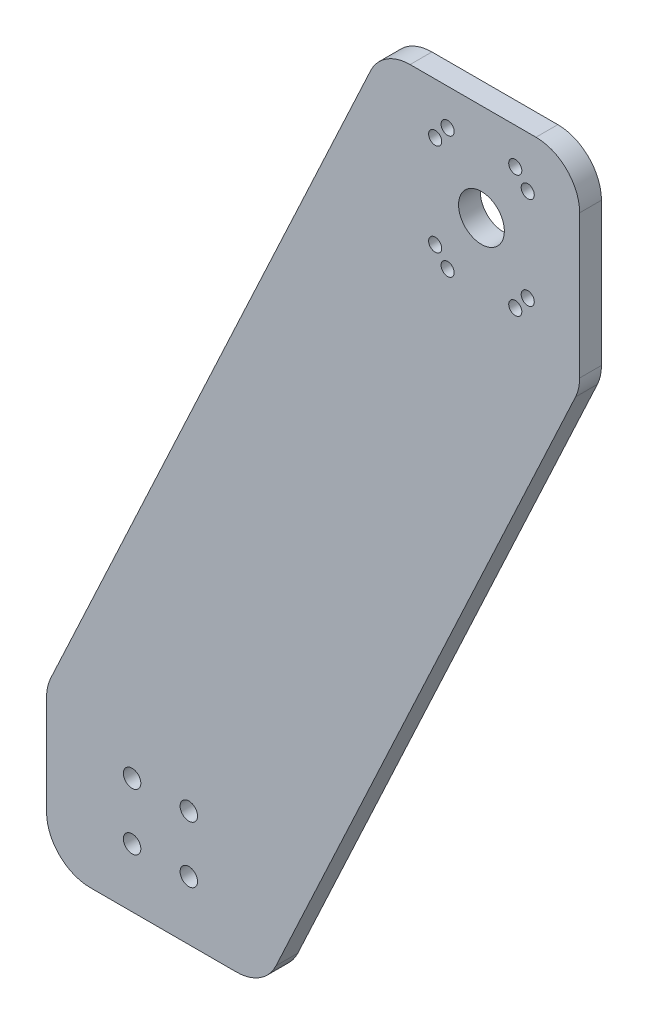
SolidWorks part; units mm, degrees
ref_plane "Piano frontale" through (0, 0, 0) normal (0, 0, 1) x (1, 0, 0)
ref_plane "Piano superiore" through (0, 0, 0) normal (0, 1, 0) x (1, 0, 0)
ref_plane "Piano destro" through (0, 0, 0) normal (1, 0, 0) x (0, 0, -1)
sketch "Schizzo1" plane through (0, 0, 0) normal (0, 0, 1) x (1, 0, 0)
  line L0 (20, 0) -> (87.0224, 0)
  line L1 (105.1486, 11.5476) -> (242.4453, 305.9815)
  line L2 (244.3192, 314.4339) -> (244.3192, 380)
  line L3 (224.3192, 400) -> (166.6229, 400)
  line L4 (0, 65.5661) -> (0, 20)
  line L5 (148.4968, 388.4524) -> (1.8738, 74.0185)
  line L6 (217.8585, 395.2269) -> (-13.8202, -101.6096) construction
  line L7 (11.433, 40) -> (107.7325, 40) construction
  line L8 (52.2134, 40) -> (52.2134, 85.084) construction
  line L9 (199.3192, 355.4693) -> (170.8286, 383.9599) construction
  line L10 (199.3192, 355.4693) -> (160.9701, 355.4693) construction
  line L11 (199.3192, 355.4693) -> (199.3192, 398.3848) construction
  line L13 (214.8192, 327.4693) -> (183.8192, 327.4693) construction
  line L14 (214.8192, 327.4693) -> (214.8192, 383.4693) construction
  line L15 (214.8192, 383.4693) -> (183.8192, 383.4693) construction
  line L16 (183.8192, 327.4693) -> (183.8192, 383.4693) construction
  line L17 (214.8192, 327.4693) -> (183.8192, 383.4693) construction
  line L18 (214.8192, 383.4693) -> (183.8192, 327.4693) construction
  circle A0 centre (39.2134, 53) radius 4
  circle A1 centre (65.2134, 53) radius 4
  circle A2 centre (65.2134, 27) radius 4
  circle A3 centre (39.2134, 27) radius 4
  circle A4 centre (199.3192, 355.4693) radius 10.5
  circle A5 centre (199.3192, 355.4693) radius 30 construction
  arc A6 (105.1486, 11.5476) -> (87.0224, 0) centre (87.0224, 20) cw
  arc A7 (20, 0) -> (0, 20) centre (20, 20) cw
  arc A8 (0, 65.5661) -> (1.8738, 74.0185) centre (20, 65.5661) cw
  arc A9 (244.3192, 314.4339) -> (242.4453, 305.9815) centre (224.3192, 314.4339) cw
  arc A10 (244.3192, 380) -> (224.3192, 400) centre (224.3192, 380) ccw
  arc A11 (166.6229, 400) -> (148.4968, 388.4524) centre (166.6229, 380) ccw
  circle A12 centre (183.8192, 383.4693) radius 3
  circle A13 centre (214.8192, 383.4693) radius 3
  circle A14 centre (220.5324, 376.6825) radius 3
  circle A15 centre (220.5324, 334.2561) radius 3
  circle A16 centre (214.8192, 327.4693) radius 3
  circle A17 centre (183.8192, 327.4693) radius 3
  circle A18 centre (178.106, 334.2561) radius 3
  circle A19 centre (178.106, 376.6825) radius 3
  point P27 (178.106, 376.6825)
  point P28 (220.5324, 376.6825)
  point P29 (220.5324, 334.2561)
  point P30 (178.106, 334.2561)
  point P39 (0, 0)
  point P42 (0, 70)
  point P45 (244.3192, 310)
  point P48 (244.3192, 400)
  dimension "D6" = 8
  dimension "D7" = 13
  dimension "D9" = 21
  dimension "D11" = 45
  dimension "D14" = 20
  dimension "D15" = 6
  dimension "D16" = 40
  dimension "D17" = 60
  dimension "D1" = 115
  dimension "D2" = 120
  dimension "D3" = 70
  dimension "D4" = 400
  dimension "D5" = 90
  dimension "D8" = 13
  dimension "D10" = 45
  dimension "D12" = 31
  dimension "D13" = 56
extrude "Estrusione-Estrusione2" add sketch "Schizzo1" against normal blind 10
sketch "Schizzo2" plane through (0, 0, 0) normal (0, -1, 0) x (1, 0, 0)
  line L0 (20, -5) -> (87.0224, -5) construction
  line L1 (20, -10) -> (20, 0) construction
  line L2 (87.0224, -10) -> (87.0224, 0) construction
  line L3 (53.5112, -5) -> (53.5112, 0) construction
  line L4 (20, 0) -> (87.0224, 0) construction
  circle A0 centre (53.5112, -5) radius 2
  circle A1 centre (81.0112, -5) radius 2
  circle A2 centre (26.0112, -5) radius 2
  dimension "D1" = 4
  dimension "D2" = 27.5
extrude "Taglio-Estrusione1" cut sketch "Schizzo2" against normal blind 15
